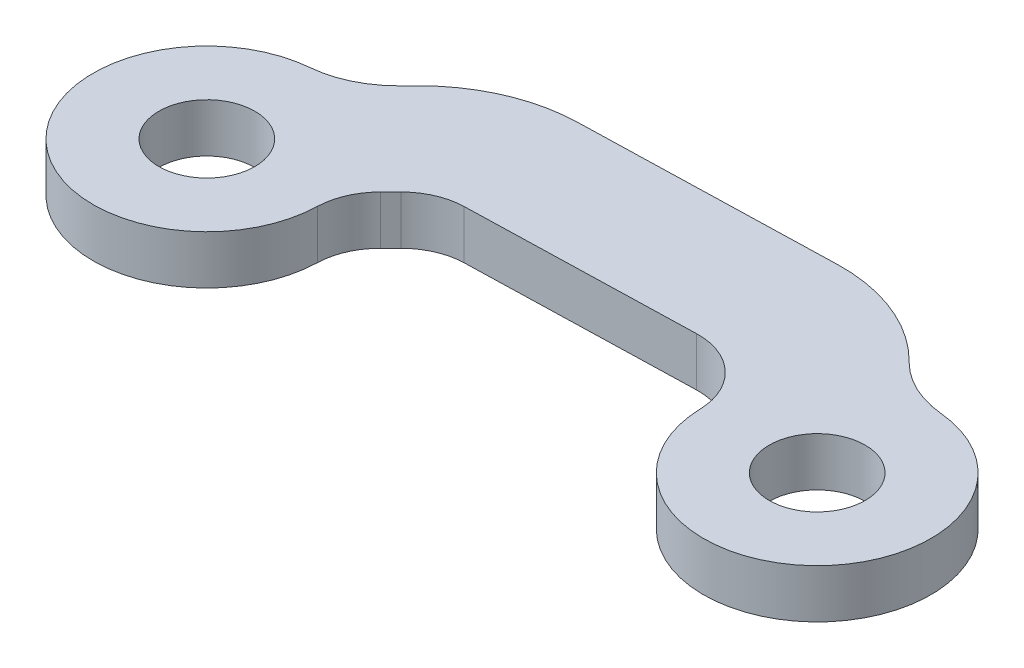
SolidWorks part; units mm, degrees
ref_plane "Front Plane" through (0, 0, 0) normal (0, 0, 1) x (1, 0, 0)
ref_plane "Top Plane" through (0, 0, 0) normal (0, 1, 0) x (1, 0, 0)
ref_plane "Right Plane" through (0, 0, 0) normal (1, 0, 0) x (0, 0, -1)
sketch "Sketch1" plane through (0, 0, 0) normal (0, 1, 0) x (1, 0, 0)
  line L0 (14.0353, 5.4617) -> (21.1066, 5.6521)
  line L1 (13.5212, 9.5134) -> (21.4341, 9.7264)
  line L2 (25.211, 8.1921) -> (25.1629, 8.2403)
  line L3 (12.3324, 4.5466) -> (12.6531, 4.8673)
  line L4 (22.6092, 5.0466) -> (22.5982, 5.0577)
  line L5 (9.7306, 7.6922) -> (10.0658, 8.0273)
  arc A0 (7.8561, 6.8124) -> (11.7381, 3.1686) centre (8.1836, 3.2715) ccw
  arc A1 (23.2035, 3.6686) -> (27.0856, 7.3123) centre (26.758, 3.7715) ccw
  circle A2 centre (8.1836, 3.2715) radius 1.5
  circle A3 centre (26.758, 3.7715) radius 1.5
  arc A4 (25.1629, 8.2403) -> (21.4341, 9.7264) centre (21.5708, 4.6482) ccw
  arc A5 (13.5212, 9.5134) -> (10.0658, 8.0273) centre (13.6579, 4.4352) ccw
  arc A6 (22.5982, 5.0577) -> (21.1066, 5.6521) centre (21.1613, 3.6208) ccw
  arc A7 (12.6531, 4.8673) -> (14.0353, 5.4617) centre (14.09, 3.4305) cw
  arc A8 (25.211, 8.1921) -> (27.0856, 7.3123) centre (27.3663, 10.3474) ccw
  arc A9 (9.7306, 7.6922) -> (7.8561, 6.8124) centre (7.5754, 9.8474) cw
  arc A10 (12.3324, 4.5466) -> (11.7381, 3.1686) centre (13.7693, 3.1098) ccw
  arc A11 (22.6092, 5.0466) -> (23.2035, 3.6686) centre (21.1724, 3.6098) cw
extrude "Boss-Extrude1" add sketch "Sketch1" along normal blind 1.524
